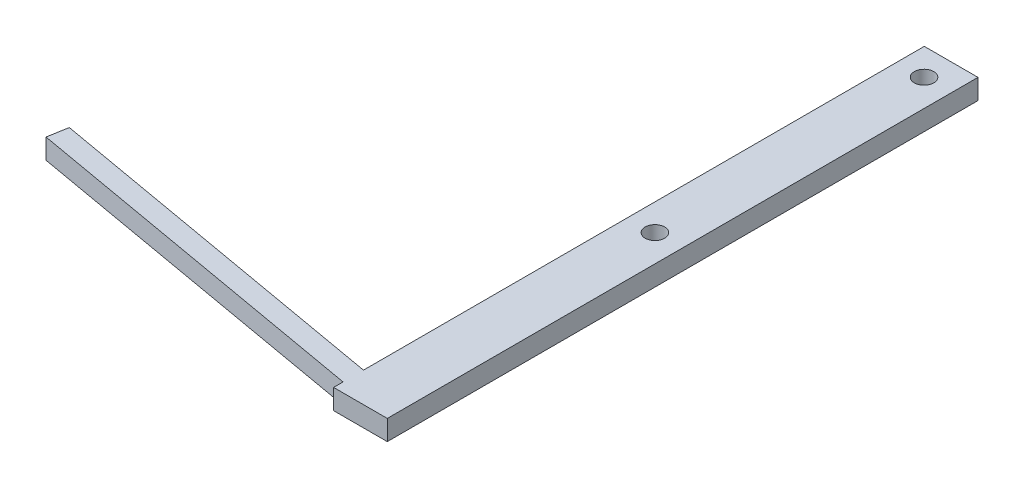
SolidWorks part; units mm, degrees
ref_plane "Front Plane" through (0, 0, 0) normal (0, 0, 1) x (1, 0, 0)
ref_plane "Top Plane" through (0, 0, 0) normal (0, 1, 0) x (1, 0, 0)
ref_plane "Right Plane" through (0, 0, 0) normal (1, 0, 0) x (0, 0, -1)
sketch "Sketch1" plane through (0, 0, 0) normal (0, 1, 0) x (1, 0, 0)
  line L1 (0, 101.5375) -> (12.7, 101.5375)
  line L2 (0, 101.5375) -> (0, -38.1625)
  line L3 (0, -38.1625) -> (12.7, -38.1625)
  line L4 (12.7, 101.5375) -> (12.7, -38.1625)
  circle A0 centre (6.2932, 95.1875) radius 2.31
  circle A5 centre (6.2932, 31.5375) radius 2.31
  dimension "D1" = 12.7
  dimension "D2" = 139.7
extrude "Boss-Extrude1" add sketch "Sketch1" along normal blind 4.7625
sketch "Sketch2" plane through (0, 0, 0) normal (0, -1, 0) x (1, 0, 0)
  line L0 (12.7, 38.1625) -> (-85.2884, 20.8845)
  line L1 (-85.2884, 20.8845) -> (-84.4614, 16.1943)
  line L2 (-84.4614, 16.1943) -> (12.7, 33.3265)
  line L3 (12.7, 33.3265) -> (12.7, 38.1625)
  line L4 (0, 38.1625) -> (0, -101.5375)
  line L5 (0, -101.5375) -> (12.7, -101.5375)
  line L6 (12.7, -101.5375) -> (12.7, 38.1625)
  line L7 (12.7, 38.1625) -> (0, 38.1625)
  line L8 (0, 38.1625) -> (0, -101.5375)
  line L9 (0, -101.5375) -> (12.7, -101.5375)
  line L10 (12.7, -101.5375) -> (12.7, 38.1625)
  line L11 (12.7, 38.1625) -> (0, 38.1625)
  line M6 (0, 38.1625) -> (0, -101.5375)
  dimension "D2" = 99.5
  dimension "D3" = 4.7625
  dimension "D4" = 80
  dimension "D1" = 0
extrude "Boss-Extrude2" add sketch "Sketch2" against normal up to surface (4.7625 mm away) contours L1 L2 L0 M6 up to face at (6.2932, 4.7625, -92.8775)
